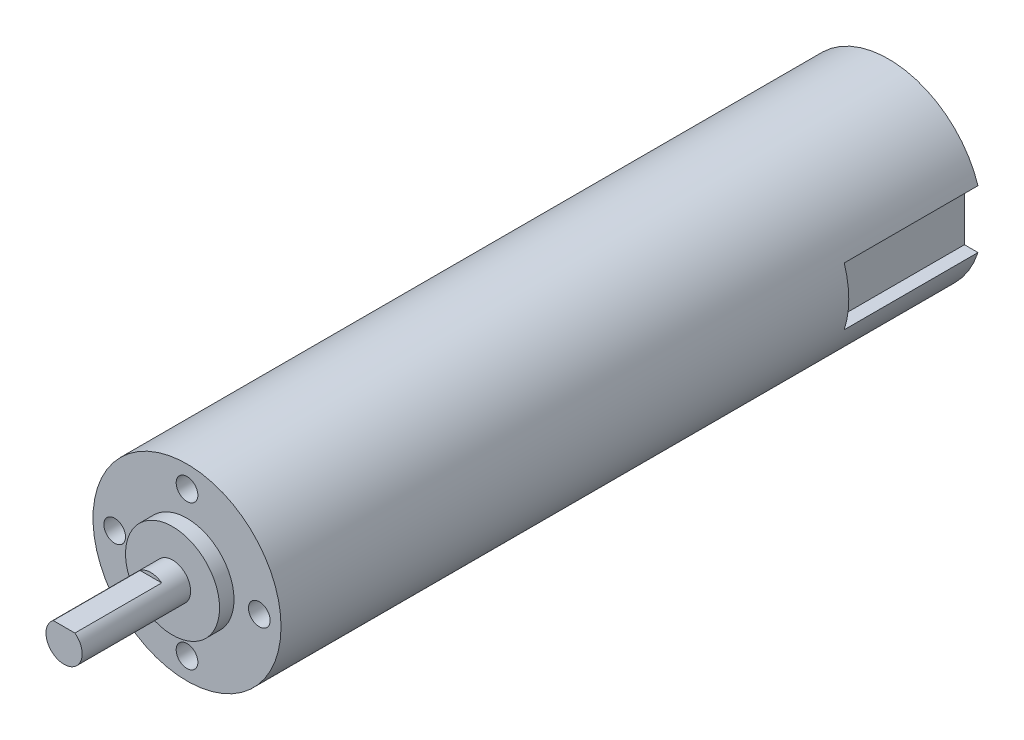
SolidWorks part; units mm, degrees
ref_plane "Plan de face" through (0, 0, 0) normal (0, 0, 1) x (1, 0, 0)
ref_plane "Plan de dessus" through (0, 0, 0) normal (0, 1, 0) x (1, 0, 0)
ref_plane "Plan de droite" through (0, 0, 0) normal (1, 0, 0) x (0, 0, -1)
sketch "Esquisse1" plane through (0, 0, 0) normal (0, 0, 1) x (1, 0, 0)
  circle A0 centre (0, 0) radius 13
  dimension "D1" = 26
extrude "Boss.-Extru.1" add sketch "Esquisse1" along normal blind 97
sketch "Esquisse2" plane through (0, 0, 97) normal (0, 0, 1) x (1, 0, 0)
  circle A0 centre (0, 0) radius 2.5
  dimension "D1" = 5
extrude "Boss.-Extru.2" add sketch "Esquisse2" along normal blind 17
sketch "Esquisse3" plane through (0, 0, 0) normal (0, 0, -1) x (-1, 0, 0)
  line L0 (-10.5, 0) -> (-10.5, 4)
  line L1 (10.5, 0) -> (13, 0) construction
  line L2 (-13, 0) -> (-10.5, 0) construction
  line L3 (-10.5, 4) -> (-12.3693, 4)
  line L4 (-10.5, 0) -> (-10.5, -4)
  line L5 (10.5, 0) -> (10.5, 4)
  line L6 (10.5, 4) -> (12.3693, 4)
  line L7 (10.5, 0) -> (10.5, -4)
  line L8 (10.5, -4) -> (12.365, -4.0133)
  line L9 (-10.5, -4) -> (-12.3693, -4)
  circle A0 centre (0, 0) radius 13 construction
  arc A1 (-12.3693, 4) -> (-12.3693, -4) centre (0, 0) ccw
  arc A2 (12.3693, 4) -> (12.365, -4.0133) centre (0, 0) cw
extrude "Enlèv. mat.-Extru.1" cut sketch "Esquisse3" against normal blind 18.5
sketch "Esquisse4" plane through (0, 0, 97) normal (0, 0, 1) x (1, 0, 0)
  circle A0 centre (0, 0) radius 6.5
  circle A1 centre (0, 0) radius 2.5
extrude "Boss.-Extru.3" add sketch "Esquisse4" along normal blind 2
sketch "Esquisse5" plane through (0, 0, 97) normal (0, 0, 1) x (1, 0, 0)
  line L0 (0, 0) -> (10, 0) construction
  line L1 (0, 0) -> (0, 10) construction
  line L2 (0, 0) -> (-10, 0) construction
  line L3 (0, 0) -> (0, -10) construction
  circle A0 centre (0, 10) radius 1.5
  circle A1 centre (-10, 0) radius 1.5
  circle A2 centre (0, -10) radius 1.5
  circle A3 centre (10, 0) radius 1.5
  dimension "D1" = 3
extrude "Enlèv. mat.-Extru.2" cut sketch "Esquisse5" against normal blind 4
sketch "Esquisse6" plane through (0, 0, 114) normal (0, 0, 1) x (1, 0, 0)
  line L0 (0, -2.5) -> (0, 2) construction
  line L1 (0, 2) -> (1.5, 2)
  line L2 (0, 2) -> (-1.5, 2)
  circle A2 centre (0, 0) radius 2.5 construction
  circle A3 centre (0, 0) radius 2.5 construction
  arc A4 (-1.5, 2) -> (1.5, 2) centre (0, 0) cw
extrude "Enlèv. mat.-Extru.3" cut sketch "Esquisse6" against normal blind 12
